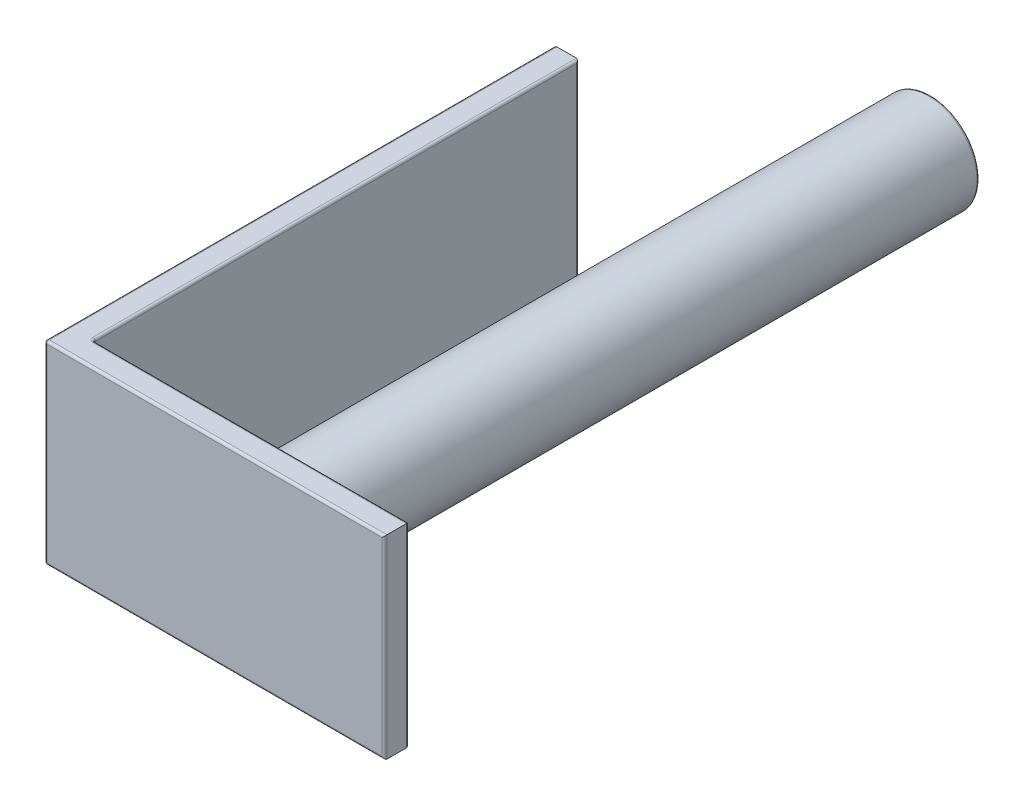
SolidWorks part; units mm, degrees
ref_plane "Front Plane" through (0, 0, 0) normal (0, 0, 1) x (1, 0, 0)
ref_plane "Top Plane" through (0, 0, 0) normal (0, 1, 0) x (1, 0, 0)
ref_plane "Right Plane" through (0, 0, 0) normal (1, 0, 0) x (0, 0, -1)
sketch "Sketch1" plane through (0, 0, 0) normal (0, 0, 1) x (1, 0, 0)
  circle A0 centre (0, 0) radius 50.8
  dimension "D1" = 101.6
extrude "Boss-Extrude1" add sketch "Sketch1" against normal blind 711.2
sketch "Sketch3" plane through (0, 0, 0) normal (0, 1, 0) x (1, 0, 0)
  line L0 (165.1, 0) -> (-165.1, 0)
  line L1 (-165.1, 0) -> (-165.1, 508)
  point P3 (0, 0)
  dimension "D1" = 330.2
  dimension "D2" = 508
extrude "Extrude-Thin1" add sketch "Sketch3" along normal mid plane 203.2 thin thin type one direction reverse wall 25.4
fillet "Fillet1" radius 2.54 16 edges at (0, -101.6, 0) (-190.5, 0, 25.4) (-12.7, 101.6, 25.4) (165.1, 0, 25.4) (-12.7, -101.6, 25.4) (50.8, 0, 0) (50.8, 0, -711.2) (-165.1, 0, 0) (-190.5, 0, -508) (-165.1, 0, -508) (165.1, 0, 0) (-165.1, -101.6, -254) (-190.5, 101.6, -241.3) (-190.5, -101.6, -241.3) (-165.1, 101.6, -254) (0, 101.6, 0)
